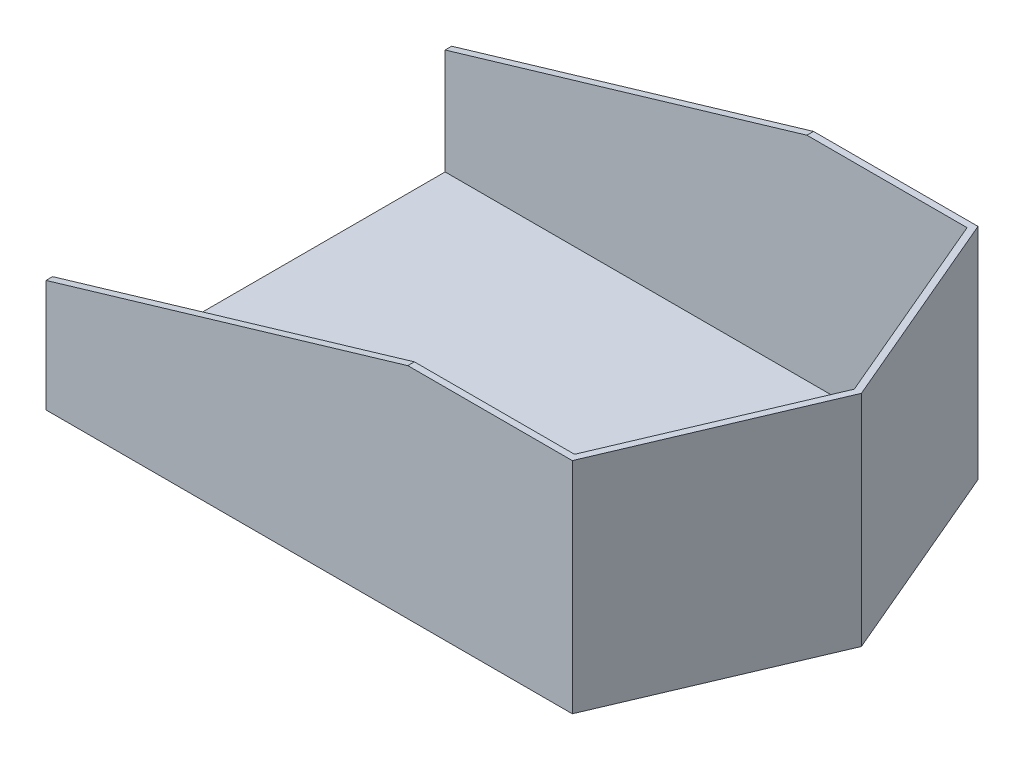
SolidWorks part; units mm, degrees
ref_plane "Front Plane" through (0, 0, 0) normal (0, 0, 1) x (1, 0, 0)
ref_plane "Top Plane" through (0, 0, 0) normal (0, 1, 0) x (1, 0, 0)
ref_plane "Right Plane" through (0, 0, 0) normal (1, 0, 0) x (0, 0, -1)
sketch "Sketch1" plane through (0, 0, 0) normal (0, 1, 0) x (1, 0, 0)
  line L0 (240, 185) -> (279.34, 92.5)
  line L1 (0, 0) -> (240, 0)
  line L2 (0, 0) -> (0, 185)
  line L3 (0, 185) -> (240, 185)
  line L5 (279.34, 92.5) -> (240, 0)
  point P5 (0, 0)
  point P7 (0, 92.5)
  dimension "D1" = 240
  dimension "D2" = 185
extrude "Boss-Extrude1" add sketch "Sketch1" along normal blind 100
shell "Shell1" thickness 3
sketch "Sketch2" plane through (0, 100, 0) normal (0, 1, 0) x (1, 0, 0)
  line L0 (0, 185) -> (0, 0) construction
  line L1 (3, 182) -> (0, 182)
  line L2 (3, 182) -> (3, 3)
  line L3 (3, 3) -> (0, 3)
  line L4 (0, 182) -> (0, 3)
extrude "Cut-Extrude1" cut sketch "Sketch2" against normal up to surface (97 mm away) up to face at (151.6223, 3, -92.5)
sketch "Sketch3" plane through (0, 0, 0) normal (0, 0, 1) x (1, 0, 0)
  line L0 (0, 100) -> (0, 51.159)
  line L1 (0, 100) -> (0, 0) construction
  line L2 (0, 51.159) -> (164.9881, 100)
  line L3 (0, 100) -> (240, 100) construction
  line L4 (164.9881, 100) -> (0, 100)
extrude "Cut-Extrude2" cut sketch "Sketch3" against normal through all
equation "\"base_width\"= 185mm"
equation "\"base_length\"= 240mm"
equation "\"D1@Sketch1\"=\"base_length\""
equation "\"D2@Sketch1\"=\"base_width\""
